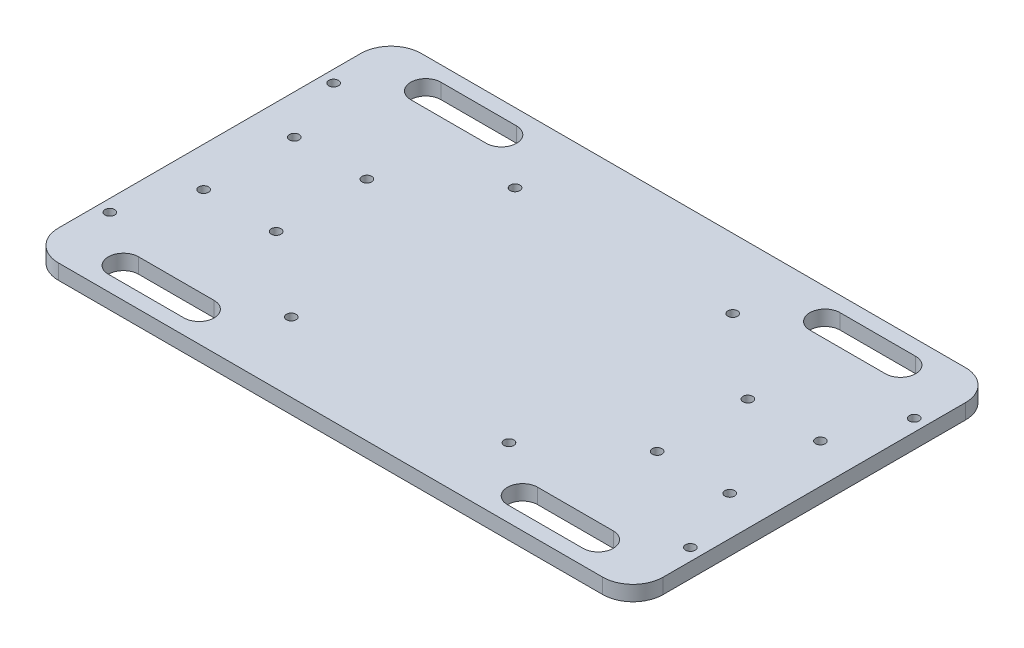
SolidWorks part; units mm, degrees
ref_plane "前视基准面" through (0, 0, 0) normal (0, 0, 1) x (1, 0, 0)
ref_plane "上视基准面" through (0, 0, 0) normal (0, 1, 0) x (1, 0, 0)
ref_plane "右视基准面" through (0, 0, 0) normal (1, 0, 0) x (0, 0, -1)
other "Configuration Table"
sketch "草图2" plane through (0, 0, 0) normal (0, 1, 0) x (1, 0, 0)
  line L0 (0, 0) -> (200, 0)
  line L1 (200, 0) -> (200, 120)
  line L2 (200, 120) -> (0, 120)
  line L3 (0, 120) -> (0, 0)
  line L4 (227.9328, 60) -> (-26.1396, 60) construction
  line L5 (100, 127.5639) -> (100, -13.5016) construction
  line L6 (153.5, 110) -> (178.5, 110) construction
  line L7 (153.5, 10) -> (178.5, 10) construction
  line L8 (153.5, 115) -> (178.5, 115)
  line L9 (153.5, 105) -> (178.5, 105)
  line L10 (153.5, 5) -> (178.5, 5)
  line L11 (153.5, 15) -> (178.5, 15)
  line L12 (46.5, 110) -> (21.5, 110) construction
  line L13 (46.5, 115) -> (21.5, 115)
  line L14 (46.5, 105) -> (21.5, 105)
  line L15 (46.5, 10) -> (21.5, 10) construction
  line L16 (46.5, 5) -> (21.5, 5)
  line L17 (46.5, 15) -> (21.5, 15)
  circle A0 centre (187, 45) radius 1.6
  circle A1 centre (187, 75) radius 1.6
  circle A2 centre (163, 45) radius 1.6
  circle A3 centre (163, 75) radius 1.6
  circle A4 centre (13, 45) radius 1.6
  circle A5 centre (37, 45) radius 1.6
  circle A6 centre (13, 75) radius 1.6
  circle A7 centre (37, 75) radius 1.6
  circle A8 centre (196, 97) radius 1.6
  circle A9 centre (136, 97) radius 1.6
  circle A10 centre (196, 23) radius 1.6
  circle A11 centre (136, 23) radius 1.6
  circle A12 centre (4, 23) radius 1.6
  circle A13 centre (4, 97) radius 1.6
  circle A14 centre (64, 23) radius 1.6
  circle A15 centre (64, 97) radius 1.6
  arc A16 (153.5, 115) -> (153.5, 105) centre (153.5, 110) ccw
  arc A17 (178.5, 105) -> (178.5, 115) centre (178.5, 110) ccw
  arc A18 (153.5, 5) -> (153.5, 15) centre (153.5, 10) cw
  arc A19 (178.5, 15) -> (178.5, 5) centre (178.5, 10) cw
  arc A20 (46.5, 115) -> (46.5, 105) centre (46.5, 110) cw
  arc A21 (21.5, 105) -> (21.5, 115) centre (21.5, 110) cw
  arc A22 (46.5, 5) -> (46.5, 15) centre (46.5, 10) ccw
  arc A23 (21.5, 15) -> (21.5, 5) centre (21.5, 10) ccw
  point P43 (0, 0)
  point P44 (0, 0)
  point P45 (166, 110)
  point P50 (0, 0)
  point P53 (159.3225, 120)
  point P54 (176.5672, 120)
  point P55 (166, 10)
  point P62 (34, 110)
  point P69 (34, 10)
  dimension "D1" = 3.2
  dimension "D3" = 24
  dimension "D5" = 4
  dimension "D6" = 60
  dimension "D8" = 34
  dimension "D2" = 13
  dimension "D4" = 30
  dimension "D7" = 74
  dimension "D9" = 10
extrude "凸台-拉伸1" add sketch "草图2" along normal blind 5
fillet "圆角1" radius 10 4 edges at (0, 2.5, -120) (0, 2.5, 0) (200, 2.5, 0) (200, 2.5, -120)
